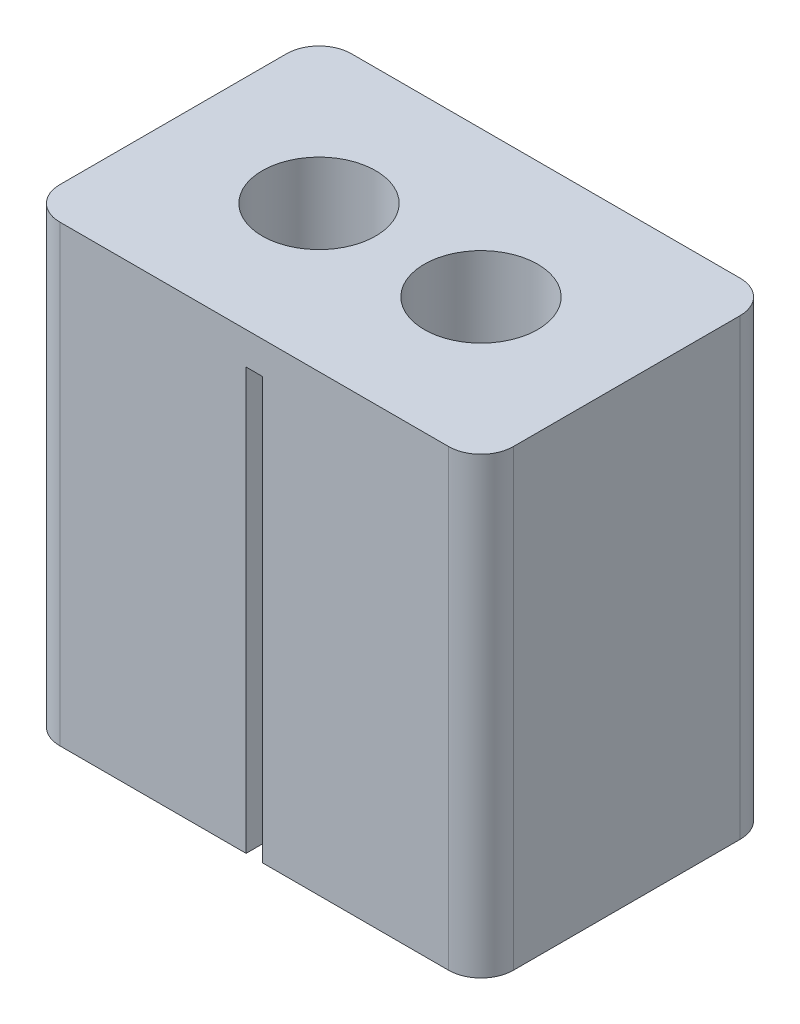
SolidWorks part; units mm, degrees
ref_plane "前视基准面" through (0, 0, 0) normal (0, 0, 1) x (1, 0, 0)
ref_plane "上视基准面" through (0, 0, 0) normal (0, 1, 0) x (1, 0, 0)
ref_plane "右视基准面" through (0, 0, 0) normal (1, 0, 0) x (0, 0, -1)
sketch "草图1" plane through (0, 0, 0) normal (0, 1, 0) x (1, 0, 0)
  line L0 (-7, 4.5) -> (7, -4.5) construction
  line L1 (-7, 4.5) -> (7, 4.5)
  line L2 (-7, 4.5) -> (-7, -4.5)
  line L3 (-7, -4.5) -> (7, -4.5)
  line L4 (7, 4.5) -> (7, -4.5)
  dimension "D1" = 9
  dimension "D2" = 14
extrude "凸台-拉伸1" add sketch "草图1" along normal blind 14
fillet "圆角1" radius 1 4 edges at (-7, 7, -4.5) (7, 7, -4.5) (7, 7, 4.5) (-7, 7, 4.5)
sketch "草图3" plane through (0, 14, 0) normal (0, 1, 0) x (1, 0, 0)
  line L0 (-2.5, 0) -> (2.5, 0) construction
  circle A0 centre (-2.5, 0) radius 1.75
  circle A1 centre (2.5, 0) radius 1.75
  point P2 (0, 0)
  dimension "D2" = 3.5
  dimension "D1" = 5
extrude "切除-拉伸2" cut sketch "草图3" against normal blind 7
sketch "草图4" plane through (0, 7, 0) normal (0, 1, 0) x (1, 0, 0)
  circle A0 centre (-2.5, 0) radius 0.95
  circle A1 centre (-2.5, 0) radius 1.75
  circle A2 centre (-2.5, 0) radius 1.75 construction
  circle A3 centre (2.5, 0) radius 1.75
  circle A4 centre (2.5, 0) radius 1.75 construction
  circle A5 centre (2.5, 0) radius 0.95
  dimension "D3" = 1.9
  dimension "D1" = 0
  dimension "D2" = 0
extrude "切除-拉伸3" cut sketch "草图4" against normal up to next
sketch "草图6" plane through (0, 14, 0) normal (0, 1, 0) x (1, 0, 0)
  line L0 (6, 4.5) -> (-6, 4.5) construction
  line L1 (-0.25, -4.5) -> (0.25, -4.5)
  line L2 (-0.25, -4.5) -> (-0.25, 4.5)
  line L3 (-0.25, 4.5) -> (0.25, 4.5)
  line L4 (0.25, -4.5) -> (0.25, 4.5)
  line L5 (-0.25, -4.5) -> (0.25, 4.5) construction
  line L6 (-0.25, 4.5) -> (0.25, -4.5) construction
  point P0 (0, 0)
  dimension "D1" = 0.5
extrude "切除-拉伸4" cut sketch "草图6" against normal up to next from offset 1
